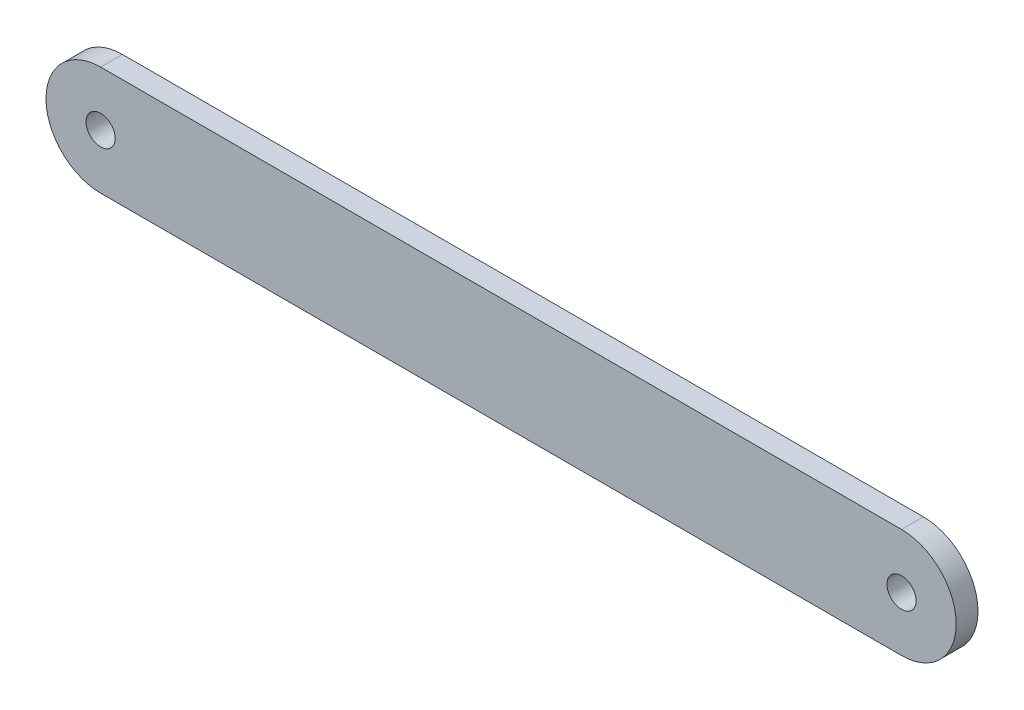
SolidWorks part; units mm, degrees
ref_plane "Front Plane" through (0, 0, 0) normal (0, 0, 1) x (1, 0, 0)
ref_plane "Top Plane" through (0, 0, 0) normal (0, 1, 0) x (1, 0, 0)
ref_plane "Right Plane" through (0, 0, 0) normal (1, 0, 0) x (0, 0, -1)
sketch "Sketch1" plane through (0, 0, 0) normal (0, 0, 1) x (1, 0, 0)
  line L0 (0, 0) -> (110, 0) construction
  line L1 (0, 7.5) -> (110, 7.5)
  line L2 (0, -7.5) -> (110, -7.5)
  arc A0 (0, 7.5) -> (0, -7.5) centre (0, 0) ccw
  arc A1 (110, -7.5) -> (110, 7.5) centre (110, 0) ccw
  circle A2 centre (0, 0) radius 2
  circle A3 centre (110, 0) radius 2
  point P3 (55, 0)
  dimension "D1" = 7.5
  dimension "D3" = 4
  dimension "D4" = 4
  dimension "D2" = 110
extrude "Boss-Extrude1" add sketch "Sketch1" along normal blind 3
